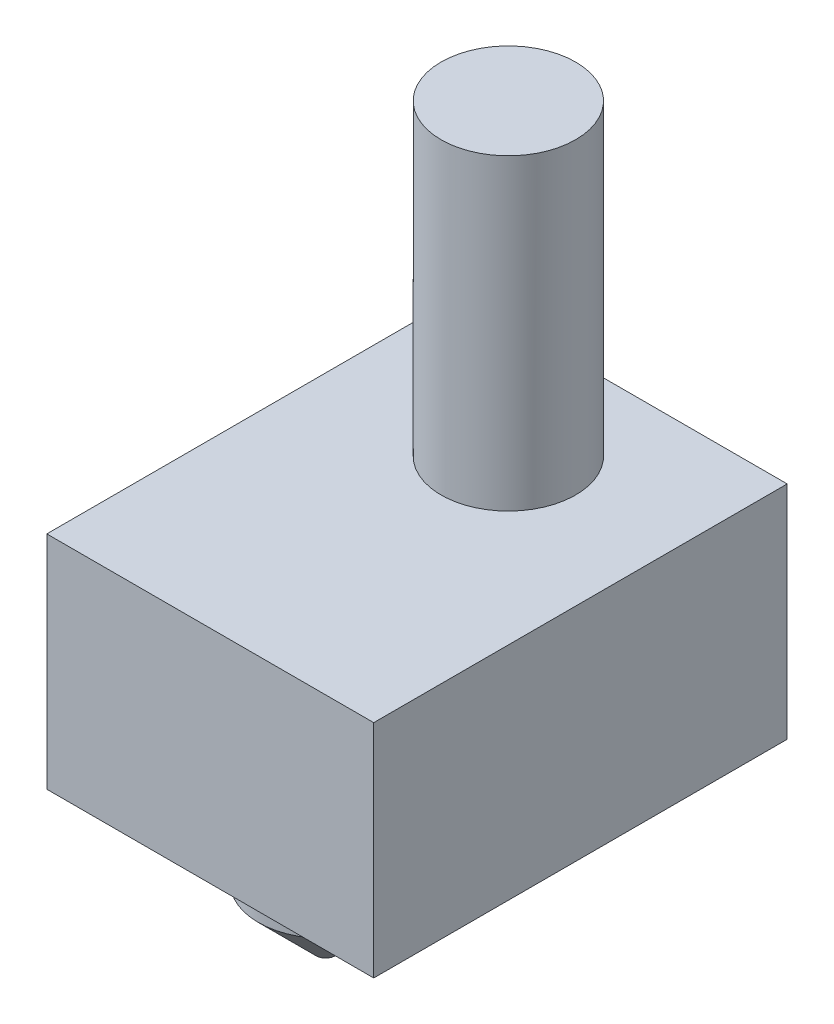
SolidWorks part; units mm, degrees
ref_plane "Front Plane" through (0, 0, 0) normal (0, 0, 1) x (1, 0, 0)
ref_plane "Top Plane" through (0, 0, 0) normal (0, 1, 0) x (1, 0, 0)
ref_plane "Right Plane" through (0, 0, 0) normal (1, 0, 0) x (0, 0, -1)
sketch "Sketch1" plane through (0, 0, 0) normal (0, 1, 0) x (1, 0, 0)
  line L1 (0, 0) -> (17, 0)
  line L2 (0, 0) -> (0, 21.5)
  line L3 (0, 21.5) -> (17, 21.5)
  line L4 (17, 0) -> (17, 21.5)
  dimension "D1" = 21.5
  dimension "D2" = 17
extrude "Boss-Extrude1" add sketch "Sketch1" along normal blind 11.5
sketch "Sketch2" plane through (0, 11.5, 0) normal (0, 1, 0) x (1, 0, 0)
  line L0 (0, 21.5) -> (0, 0) construction
  line L2 (0, 0) -> (17, 0) construction
  circle A0 centre (8.5, 15.5) radius 3.5
  dimension "D1" = 7
  dimension "D2" = 8.5
  dimension "D3" = 15.5
extrude "Boss-Extrude2" add sketch "Sketch2" along normal blind 16
sketch "Sketch3" plane through (0, 0, 0) normal (0, -1, 0) x (1, 0, 0)
  line L0 (0, -21.5) -> (0, 0) construction
  line L1 (17, -21.5) -> (0, -21.5) construction
  circle A0 centre (8.5, -6) radius 3.5
  dimension "D1" = 7
  dimension "D2" = 8.5
  dimension "D3" = 15.5
extrude "Boss-Extrude3" add sketch "Sketch3" along normal blind 6
chamfer "Chamfer1" distance 3 angle 45 1 edges at (8.5, -6, -9.5)
